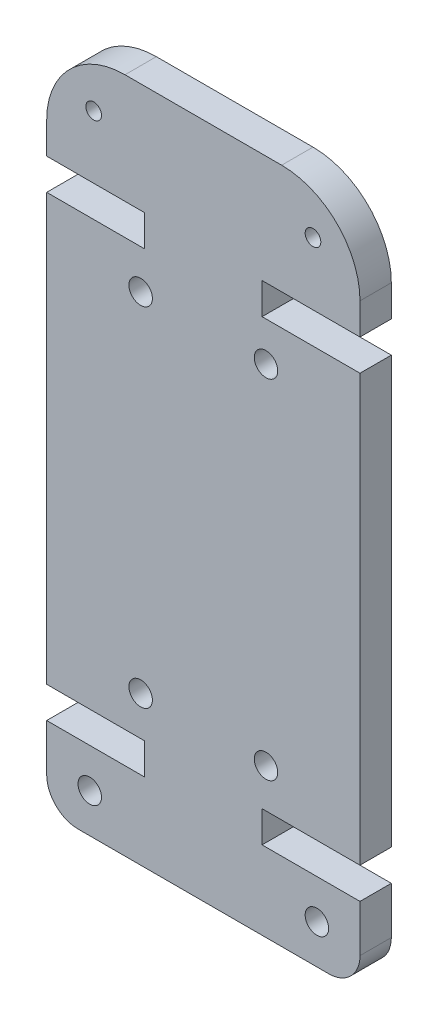
SolidWorks part; units mm, degrees
material "Acrylic (Medium-high impact)"
ref_plane "Front Plane" through (0, 0, 0) normal (0, 0, 1) x (1, 0, 0)
ref_plane "Top Plane" through (0, 0, 0) normal (0, 1, 0) x (1, 0, 0)
ref_plane "Right Plane" through (0, 0, 0) normal (1, 0, 0) x (0, 0, -1)
sketch "Model" plane through (0, 0, 0) normal (0, 0, 1) x (1, 0, 0)
  line L8 (1967.1098, 1238.3847) -> (1983.1098, 1238.3847)
  line L9 (1970.1098, 1281.5847) -> (1980.1098, 1281.5847)
  line L10 (1965.1098, 1243.3847) -> (1965.1098, 1240.3847)
  line L11 (1985.1098, 1243.3847) -> (1985.1098, 1240.3847)
  line L13 (1971.3598, 1243.3847) -> (1965.1098, 1243.3847)
  line L14 (1978.8598, 1243.3847) -> (1985.1098, 1243.3847)
  line L15 (1971.3598, 1243.3847) -> (1971.3598, 1245.3847)
  line L16 (1971.3598, 1245.3847) -> (1965.1098, 1245.3847)
  line L17 (1978.8598, 1243.3847) -> (1978.8598, 1245.3847)
  line L18 (1978.8598, 1245.3847) -> (1985.1098, 1245.3847)
  line L45 (1971.3598, 1274.5847) -> (1965.1098, 1274.5847)
  line L46 (1978.8598, 1274.5847) -> (1985.1098, 1274.5847)
  line L47 (1971.3598, 1274.5847) -> (1971.3598, 1272.5847)
  line L48 (1971.3598, 1272.5847) -> (1965.1098, 1272.5847)
  line L49 (1978.8598, 1274.5847) -> (1978.8598, 1272.5847)
  line L50 (1978.8598, 1272.5847) -> (1985.1098, 1272.5847)
  line L51 (1985.1098, 1245.3847) -> (1985.1098, 1272.5847)
  line L52 (1965.1098, 1276.5847) -> (1965.1098, 1274.5847)
  line L53 (1965.1098, 1272.5847) -> (1965.1098, 1245.3847)
  line L60 (1985.1098, 1274.5847) -> (1985.1098, 1276.5847)
  arc A10 (1983.1098, 1238.3847) -> (1985.1098, 1240.3847) centre (1983.1098, 1240.3847) ccw
  arc A11 (1965.1098, 1240.3847) -> (1967.1098, 1238.3847) centre (1967.1098, 1240.3847) ccw
  arc A12 (1970.1098, 1281.5847) -> (1965.1098, 1276.5847) centre (1970.1098, 1276.5847) ccw
  arc A13 (1985.1098, 1276.5847) -> (1980.1098, 1281.5847) centre (1980.1098, 1276.5847) ccw
  circle A14 centre (1968.1098, 1278.5847) radius 0.5
  circle A15 centre (1982.1098, 1278.5847) radius 0.5
  circle A19 centre (1979.1098, 1247.8847) radius 0.75
  circle A20 centre (1971.1098, 1247.8847) radius 0.75
  circle A96 centre (1979.1098, 1270.0847) radius 0.75
  circle A97 centre (1971.1098, 1270.0847) radius 0.75
  circle A102 centre (1982.3598, 1240.8847) radius 0.75
  circle A103 centre (1967.8598, 1240.8847) radius 0.75
extrude "Boss-Extrude1" add sketch "Model" along normal blind 2
